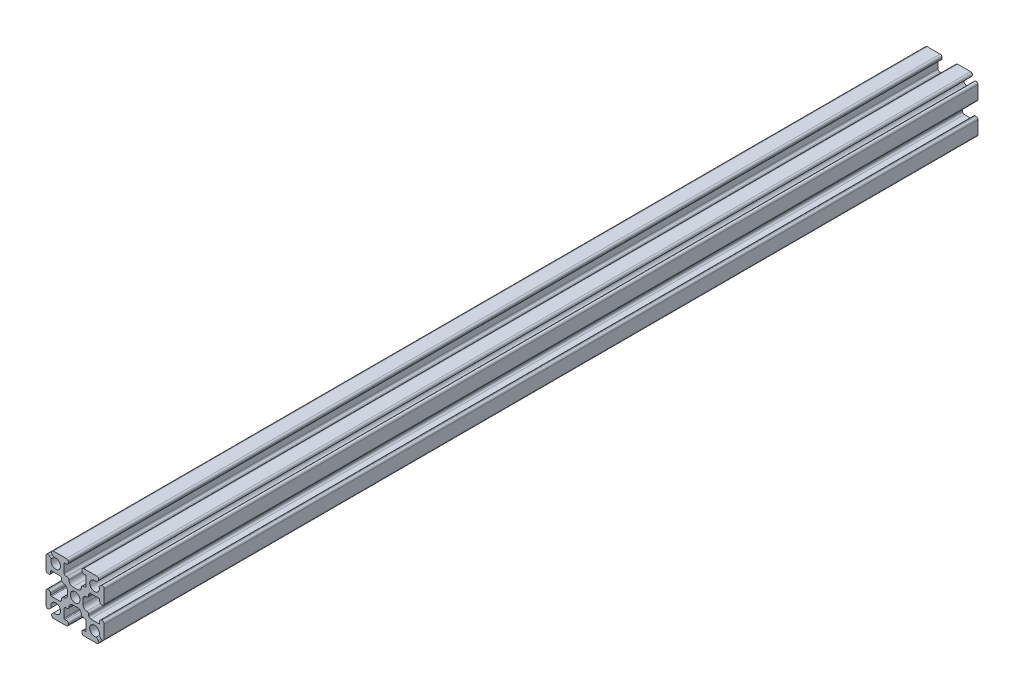
SolidWorks part; units mm, degrees
ref_plane "Front" through (0, 0, 0) normal (0, 0, 1) x (1, 0, 0)
ref_plane "Top" through (0, 0, 0) normal (0, 1, 0) x (1, 0, 0)
ref_plane "Right" through (0, 0, 0) normal (1, 0, 0) x (0, 0, -1)
sketch "Sketch1" plane through (0, 0, 0) normal (0, 0, 1) x (1, 0, 0)
  line L0 (6.6464, 5.9393) -> (6.1636, 5.4565)
  line L1 (5.4565, 6.1636) -> (5.9393, 6.6464)
  line L2 (5.5858, 7.5) -> (2.25, 7.5)
  line L3 (1.75, 7) -> (1.75, 6.8)
  line L4 (2.25, 6.3) -> (2.65, 6.3)
  line L5 (2.85, 6.1) -> (2.85, 4)
  line L6 (2.35, 3.5) -> (2.1, 3.5)
  line L7 (0.6, 2) -> (-0.6, 2)
  line L8 (-2.1, 3.5) -> (-2.35, 3.5)
  line L9 (-2.85, 4) -> (-2.85, 6.1)
  line L10 (-2.65, 6.3) -> (-2.25, 6.3)
  line L11 (-1.75, 6.8) -> (-1.75, 7)
  line L12 (-2.25, 7.5) -> (-5.5858, 7.5)
  line L13 (-5.9393, 6.6464) -> (-5.4565, 6.1636)
  line L14 (-6.1636, 5.4565) -> (-6.6464, 5.9393)
  line L15 (-7.5, 5.5858) -> (-7.5, 2.25)
  line L16 (-7, 1.75) -> (-6.8, 1.75)
  line L17 (-6.3, 2.25) -> (-6.3, 2.65)
  line L18 (-6.1, 2.85) -> (-4, 2.85)
  line L19 (-3.5, 2.35) -> (-3.5, 2.1)
  line L20 (-2, 0.6) -> (-2, -0.6)
  line L21 (-3.5, -2.1) -> (-3.5, -2.35)
  line L22 (-4, -2.85) -> (-6.1, -2.85)
  line L23 (-6.3, -2.65) -> (-6.3, -2.25)
  line L24 (-6.8, -1.75) -> (-7, -1.75)
  line L25 (-7.5, -2.25) -> (-7.5, -5.5858)
  line L26 (-6.6464, -5.9393) -> (-6.1636, -5.4565)
  line L27 (-5.4565, -6.1636) -> (-5.9393, -6.6464)
  line L28 (-5.5858, -7.5) -> (-2.25, -7.5)
  line L29 (-1.75, -7) -> (-1.75, -6.8)
  line L30 (-2.25, -6.3) -> (-2.65, -6.3)
  line L31 (-2.85, -6.1) -> (-2.85, -4)
  line L32 (-2.35, -3.5) -> (-2.1, -3.5)
  line L33 (-0.6, -2) -> (0.6, -2)
  line L34 (2.1, -3.5) -> (2.35, -3.5)
  line L35 (2.85, -4) -> (2.85, -6.1)
  line L36 (2.65, -6.3) -> (2.25, -6.3)
  line L37 (1.75, -6.8) -> (1.75, -7)
  line L38 (2.25, -7.5) -> (5.5858, -7.5)
  line L39 (5.9393, -6.6464) -> (5.4565, -6.1636)
  line L40 (6.1636, -5.4565) -> (6.6464, -5.9393)
  line L41 (7.5, -5.5858) -> (7.5, -2.25)
  line L42 (7, -1.75) -> (6.8, -1.75)
  line L43 (6.3, -2.25) -> (6.3, -2.65)
  line L44 (6.1, -2.85) -> (4, -2.85)
  line L45 (3.5, -2.35) -> (3.5, -2.1)
  line L46 (2, -0.6) -> (2, 0.6)
  line L47 (3.5, 2.1) -> (3.5, 2.35)
  line L48 (4, 2.85) -> (6.1, 2.85)
  line L49 (6.3, 2.65) -> (6.3, 2.25)
  line L50 (6.8, 1.75) -> (7, 1.75)
  line L51 (7.5, 2.25) -> (7.5, 5.5858)
  circle A0 centre (0, 0) radius 1.25
  arc A1 (6.1636, 5.4565) -> (5.4565, 6.1636) centre (5, 5) cw
  arc A2 (5.9393, 6.6464) -> (5.5858, 7.5) centre (5.5858, 7) ccw
  arc A3 (2.25, 7.5) -> (1.75, 7) centre (2.25, 7) ccw
  arc A4 (1.75, 6.8) -> (2.25, 6.3) centre (2.25, 6.8) ccw
  arc A5 (2.65, 6.3) -> (2.85, 6.1) centre (2.65, 6.1) cw
  arc A6 (2.85, 4) -> (2.35, 3.5) centre (2.35, 4) cw
  arc A7 (2.1, 3.5) -> (1.6, 3) centre (2.1, 3) ccw
  arc A8 (1.6, 3) -> (0.6, 2) centre (0.6, 3) cw
  arc A9 (-0.6, 2) -> (-1.6, 3) centre (-0.6, 3) cw
  arc A10 (-1.6, 3) -> (-2.1, 3.5) centre (-2.1, 3) ccw
  arc A11 (-2.35, 3.5) -> (-2.85, 4) centre (-2.35, 4) cw
  arc A12 (-2.85, 6.1) -> (-2.65, 6.3) centre (-2.65, 6.1) cw
  arc A13 (-2.25, 6.3) -> (-1.75, 6.8) centre (-2.25, 6.8) ccw
  arc A14 (-1.75, 7) -> (-2.25, 7.5) centre (-2.25, 7) ccw
  arc A15 (-5.5858, 7.5) -> (-5.9393, 6.6464) centre (-5.5858, 7) ccw
  arc A16 (-5.4565, 6.1636) -> (-6.1636, 5.4565) centre (-5, 5) cw
  arc A17 (-6.6464, 5.9393) -> (-7.5, 5.5858) centre (-7, 5.5858) ccw
  arc A18 (-7.5, 2.25) -> (-7, 1.75) centre (-7, 2.25) ccw
  arc A19 (-6.8, 1.75) -> (-6.3, 2.25) centre (-6.8, 2.25) ccw
  arc A20 (-6.3, 2.65) -> (-6.1, 2.85) centre (-6.1, 2.65) cw
  arc A21 (-4, 2.85) -> (-3.5, 2.35) centre (-4, 2.35) cw
  arc A22 (-3.5, 2.1) -> (-3, 1.6) centre (-3, 2.1) ccw
  arc A23 (-3, 1.6) -> (-2, 0.6) centre (-3, 0.6) cw
  arc A24 (-2, -0.6) -> (-3, -1.6) centre (-3, -0.6) cw
  arc A25 (-3, -1.6) -> (-3.5, -2.1) centre (-3, -2.1) ccw
  arc A26 (-3.5, -2.35) -> (-4, -2.85) centre (-4, -2.35) cw
  arc A27 (-6.1, -2.85) -> (-6.3, -2.65) centre (-6.1, -2.65) cw
  arc A28 (-6.3, -2.25) -> (-6.8, -1.75) centre (-6.8, -2.25) ccw
  arc A29 (-7, -1.75) -> (-7.5, -2.25) centre (-7, -2.25) ccw
  arc A30 (-7.5, -5.5858) -> (-6.6464, -5.9393) centre (-7, -5.5858) ccw
  arc A31 (-6.1636, -5.4565) -> (-5.4565, -6.1636) centre (-5, -5) cw
  arc A32 (-5.9393, -6.6464) -> (-5.5858, -7.5) centre (-5.5858, -7) ccw
  arc A33 (-2.25, -7.5) -> (-1.75, -7) centre (-2.25, -7) ccw
  arc A34 (-1.75, -6.8) -> (-2.25, -6.3) centre (-2.25, -6.8) ccw
  arc A35 (-2.65, -6.3) -> (-2.85, -6.1) centre (-2.65, -6.1) cw
  arc A36 (-2.85, -4) -> (-2.35, -3.5) centre (-2.35, -4) cw
  arc A37 (-2.1, -3.5) -> (-1.6, -3) centre (-2.1, -3) ccw
  arc A38 (-1.6, -3) -> (-0.6, -2) centre (-0.6, -3) cw
  arc A39 (0.6, -2) -> (1.6, -3) centre (0.6, -3) cw
  arc A40 (1.6, -3) -> (2.1, -3.5) centre (2.1, -3) ccw
  arc A41 (2.35, -3.5) -> (2.85, -4) centre (2.35, -4) cw
  arc A42 (2.85, -6.1) -> (2.65, -6.3) centre (2.65, -6.1) cw
  arc A43 (2.25, -6.3) -> (1.75, -6.8) centre (2.25, -6.8) ccw
  arc A44 (1.75, -7) -> (2.25, -7.5) centre (2.25, -7) ccw
  arc A45 (5.5858, -7.5) -> (5.9393, -6.6464) centre (5.5858, -7) ccw
  arc A46 (5.4565, -6.1636) -> (6.1636, -5.4565) centre (5, -5) cw
  arc A47 (6.6464, -5.9393) -> (7.5, -5.5858) centre (7, -5.5858) ccw
  arc A48 (7.5, -2.25) -> (7, -1.75) centre (7, -2.25) ccw
  arc A49 (6.8, -1.75) -> (6.3, -2.25) centre (6.8, -2.25) ccw
  arc A50 (6.3, -2.65) -> (6.1, -2.85) centre (6.1, -2.65) cw
  arc A51 (4, -2.85) -> (3.5, -2.35) centre (4, -2.35) cw
  arc A52 (3.5, -2.1) -> (3, -1.6) centre (3, -2.1) ccw
  arc A53 (3, -1.6) -> (2, -0.6) centre (3, -0.6) cw
  arc A54 (2, 0.6) -> (3, 1.6) centre (3, 0.6) cw
  arc A55 (3, 1.6) -> (3.5, 2.1) centre (3, 2.1) ccw
  arc A56 (3.5, 2.35) -> (4, 2.85) centre (4, 2.35) cw
  arc A57 (6.1, 2.85) -> (6.3, 2.65) centre (6.1, 2.65) cw
  arc A58 (6.3, 2.25) -> (6.8, 1.75) centre (6.8, 2.25) ccw
  arc A59 (7, 1.75) -> (7.5, 2.25) centre (7, 2.25) ccw
  arc A60 (7.5, 5.5858) -> (6.6464, 5.9393) centre (7, 5.5858) ccw
extrude "Boss-Extrude1" add sketch "Sketch1" along normal blind 225
